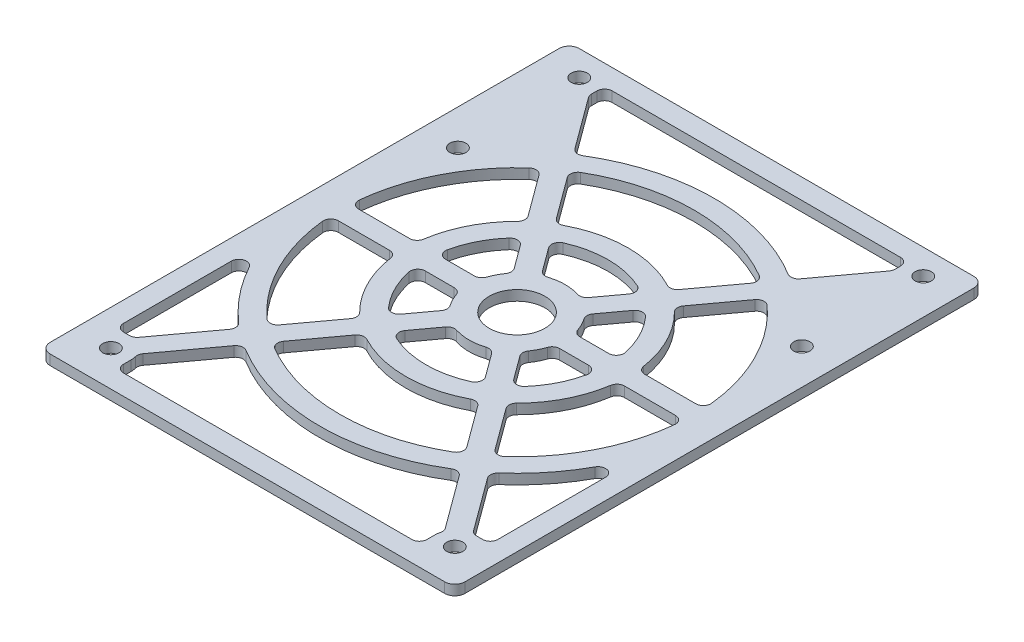
SolidWorks part; units mm, degrees
material "Thornel Mat VMA"
ref_plane "前视基准面" through (0, 0, 0) normal (0, 0, 1) x (1, 0, 0)
ref_plane "上视基准面" through (0, 0, 0) normal (0, 1, 0) x (1, 0, 0)
ref_plane "右视基准面" through (0, 0, 0) normal (1, 0, 0) x (0, 0, -1)
other "Configuration Table"
sketch "草图1" plane through (0, 0, 0) normal (0, 1, 0) x (1, 0, 0)
  line L1 (-41, 52.3) -> (41, 52.3)
  line L2 (-41, 52.3) -> (-41, -52.3)
  line L3 (-41, -52.3) -> (41, -52.3)
  line L4 (41, 52.3) -> (41, -52.3)
  line L5 (-41, 52.3) -> (41, -52.3) construction
  line L6 (-41, -52.3) -> (41, 52.3) construction
  point P0 (0, 0)
  dimension "D1" = 82
  dimension "D2" = 104.6
extrude "凸台-拉伸1" add sketch "草图1" along normal blind 2
sketch "草图2" plane through (0, 2, 0) normal (0, 1, 0) x (1, 0, 0)
  line L0 (-41, 52.3) -> (-41, -52.3) construction
  line L1 (-41, -52.3) -> (41, -52.3) construction
  line L2 (41, -52.3) -> (41, 52.3) construction
  line L3 (41, 52.3) -> (-41, 52.3) construction
  circle A0 centre (-34, -45.3) radius 1.6
  circle A1 centre (-34, 23.3) radius 1.6
  circle A2 centre (34, 47.3) radius 1.6
  circle A3 centre (34, -45.3) radius 1.6
  circle A4 centre (34, 23.3) radius 1.6
  dimension "D3" = 3.2
  dimension "D1" = 7
  dimension "D2" = 7
  dimension "D4" = 7
  dimension "D5" = 5
  dimension "D6" = 68.6
extrude "切除-拉伸1" cut sketch "草图2" against normal blind 10
sketch "草图3" plane through (0, 2, 0) normal (0, 1, 0) x (1, 0, 0)
  line L0 (-41, -52.3) -> (41, -52.3) construction
  line L1 (-37, 48.3) -> (37, 48.3)
  line L2 (-37, 48.3) -> (-37, -48.3)
  line L3 (-37, -48.3) -> (37, -48.3)
  line L4 (37, 48.3) -> (37, -48.3)
  line L5 (-37, 48.3) -> (37, -48.3) construction
  line L6 (-37, -48.3) -> (37, 48.3) construction
  line L7 (-30, -45.3) -> (-30, -48.3)
  line L8 (41, -52.3) -> (41, 52.3) construction
  line L9 (30, 23.3) -> (30, 48.3)
  line L10 (-30, 23.3) -> (-30, 48.3)
  line L11 (-34, -41.3) -> (-37, -41.3)
  line L12 (30, -45.3) -> (30, -48.3)
  line L13 (34, -41.3) -> (37, -41.3)
  line L14 (-34, 19.3) -> (-37, 19.3)
  line L15 (34, 19.3) -> (37, 19.3)
  circle A1 centre (34, -45.3) radius 4
  circle A2 centre (-34, -45.3) radius 4
  circle A3 centre (-34, 23.3) radius 4
  circle A4 centre (34, 23.3) radius 4
  point P0 (0, 0)
  dimension "D3" = 8
  dimension "D1" = 4
  dimension "D2" = 4
extrude "切除-拉伸2" cut sketch "草图3" against normal blind 10 contours A4 L9 L1 L10 A3 L14 L2 L11 A2 L7 L3 L12 A1 L13 L4 L15
sketch "草图4" plane through (0, 2, 0) normal (0, 1, 0) x (1, 0, 0)
  line L1 (-30, -48.3) -> (30, -48.3) construction
  line L2 (34, 23.3) -> (-34, -45.3)
  line L3 (34, -45.3) -> (-34, 23.3)
  line L4 (-37, -11) -> (37, -11)
  line L5 (-37, 19.3) -> (-37, -41.3) construction
  line L6 (37, 19.3) -> (37, -41.3) construction
  circle A0 centre (0, -12.5) radius 36
  circle A1 centre (0, -11) radius 15
  dimension "D2" = 72
  dimension "D3" = 30
  dimension "D1" = 35.8
extrude "拉伸-薄壁1" [suppressed] add sketch "草图4" against normal blind 2 thin contours A0 | A1 | L4 | L2 | L3
sketch "草图5" plane through (0, 2, 0) normal (0, 1, 0) x (1, 0, 0)
  line L0 (34, 47.3) -> (-34, -45.3)
  line L1 (34, -45.3) -> (-34, 47.3)
  line L2 (37, 1) -> (-37, 1)
  line L3 (37, 19.3) -> (37, -41.3) construction
  line L4 (-37, 19.3) -> (-37, -41.3) construction
  circle A0 centre (0, 1) radius 37
  circle A1 centre (0, 1) radius 20
  circle A2 centre (0, 1) radius 7.5
  dimension "D1" = 40
  dimension "D2" = 15
extrude "拉伸-薄壁2" add sketch "草图5" against normal blind 2 thin contours L1 | L0 | L2 | A2 | A1 | A0 thin type mid plane wall 4
sketch "草图6" plane through (0, 2, 0) normal (0, 1, 0) x (1, 0, 0)
  line L2 (-37, 19.3) -> (-37, 13.3288)
  line L3 (-34.4399, 19.3) -> (-37, 19.3)
  line L4 (-37, 19.3) -> (-37, 13.3288)
  line L5 (-34.4399, 19.3) -> (-37, 19.3)
  line L6 (-30, 38.4739) -> (-30, 25.9199)
  line L7 (-24.6654, 31.2095) -> (-30, 38.4739)
  line L8 (-30, 38.4739) -> (-30, 25.9199)
  line L9 (-24.6654, 31.2095) -> (-30, 38.4739)
  line L10 (37, 13.3288) -> (37, 19.3)
  line L11 (37, 19.3) -> (34.4399, 19.3)
  line L12 (37, 13.3288) -> (37, 19.3)
  line L13 (37, 19.3) -> (34.4399, 19.3)
  line L14 (30, 38.4739) -> (24.6654, 31.2095)
  line L15 (30, 25.9199) -> (30, 38.4739)
  line L16 (30, 38.4739) -> (24.6654, 31.2095)
  line L17 (30, 25.9199) -> (30, 38.4739)
  arc A1 (-24.6654, 31.2095) -> (-30, 25.9199) centre (0, 1) ccw
  arc A3 (-34.4399, 19.3) -> (-37, 13.3288) centre (0, 1) ccw
  arc A5 (-34.4399, 19.3) -> (-37, 13.3288) centre (0, 1) ccw
  arc A6 (-24.6654, 31.2095) -> (-30, 25.9199) centre (0, 1) ccw
  arc A7 (30, 25.9199) -> (24.6654, 31.2095) centre (0, 1) ccw
  arc A8 (37, 13.3288) -> (34.4399, 19.3) centre (0, 1) ccw
  arc A10 (37, 13.3288) -> (34.4399, 19.3) centre (0, 1) ccw
  arc A12 (30, 25.9199) -> (24.6654, 31.2095) centre (0, 1) ccw
  dimension "D1" = 0
  dimension "D2" = 0
  dimension "D3" = 0
  dimension "D4" = 0
extrude "凸台-拉伸2" add sketch "草图6" against normal blind 2
sketch "草图7" plane through (0, 2, 0) normal (0, 1, 0) x (1, 0, 0)
  line L0 (35.2896, -44.353) -> (32.7104, -46.247) construction
  line L1 (-32.7104, -46.247) -> (-35.2896, -44.353) construction
  line L2 (32.7104, 48.247) -> (35.2896, 46.353) construction
  circle A0 centre (0, 1) radius 5.5
  circle A1 centre (34, -45.3) radius 1.6
  circle A2 centre (-34, -45.3) radius 1.6
  circle A3 centre (34, 47.3) radius 1.6
  circle A4 centre (-34, 47.3) radius 1.6
extrude "切除-拉伸3" cut sketch "草图7" against normal blind 2
fillet "圆角1" radius 1.5 68 edges at (-7.109, 1, -7.3018) (3.8849, 1, 7.6693) (-12.2001, 1, -14.2347) (8.976, 1, 14.6023) (-8.976, 1, 14.6023) (12.2001, 1, -14.2347) (-14.5797, 1, -17.4752) (11.3557, 1, 17.8427) (-22.2944, 1, -27.9807) (19.0703, 1, 28.3483) (-19.0703, 1, 28.3483) (22.2944, 1, -27.9807) (-11.3557, 1, 17.8427) (14.5797, 1, -17.4752) (-14.5797, 1, 15.4752) (11.3557, 1, -19.8427) (-11.3557, 1, -19.8427) (14.5797, 1, 15.4752) (-19.0703, 1, -30.3483) (22.2944, 1, 25.9807) (-22.2944, 1, 25.9807) (19.0703, 1, -30.3483) (-7.109, 1, 5.3018) (3.8849, 1, -9.6693) (-3.8849, 1, -9.6693) (7.109, 1, 5.3018) (-8.976, 1, -16.6023) (12.2001, 1, 12.2347) (-12.2001, 1, 12.2347) (8.976, 1, -16.6023) (-21.9089, 1, 1) (21.9089, 1, 1) (-34.9428, 1, 1) (34.9428, 1, 1) (-9.2871, 1, 1) (9.2871, 1, 1) (-17.8885, 1, 1) (17.8885, 1, 1) (-21.9089, 1, -3) (21.9089, 1, -3) (-34.9428, 1, -3) (34.9428, 1, -3) (-9.2871, 1, -3) (9.2871, 1, -3) (-3.8849, 1, 7.6693) (7.109, 1, -7.3018) (-17.8885, 1, -3) (17.8885, 1, -3) (24.6654, 1, 29.2095) (-21.4414, 1, -33.5771) (37, 1, 11.3288) (37, 1, 41.3) (33.5617, 1, 41.3241) (-24.6654, 1, 29.2095) (21.4414, 1, -33.5771) (-30, 1, -45.2319) (-30, 1, -48.3) (30, 1, -48.3) (30, 1, -45.2319) (-33.5617, 1, 41.3241) (-37, 1, 41.3) (-37, 1, 11.3288) (-21.4414, 1, 31.5771) (21.4414, 1, 31.5771) (30.3376, 1, 43.6917) (30, 1, 48.3) (-30, 1, 48.3) (-30.3376, 1, 43.6917)
fillet "圆角2" radius 2 4 edges at (41, 1, 52.3) (-41, 1, 52.3) (-41, 1, -52.3) (41, 1, -52.3)
